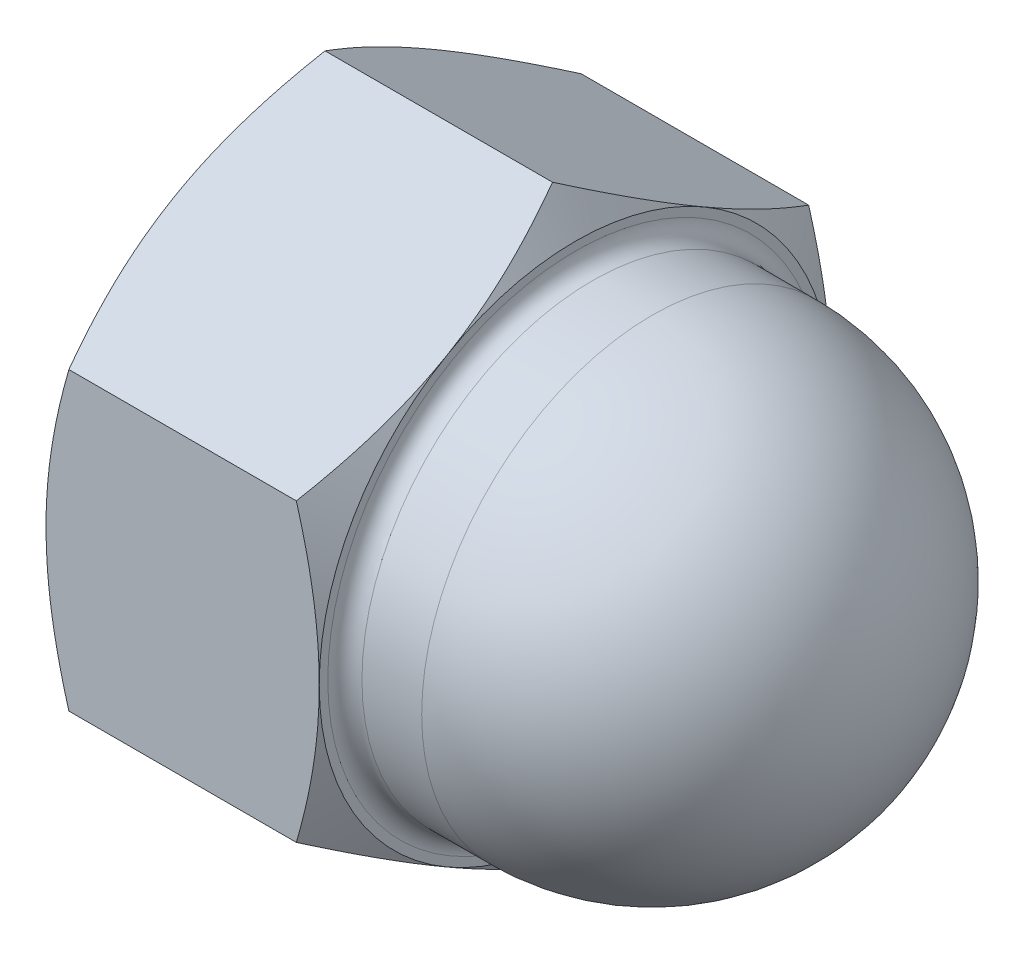
SolidWorks part; units mm, degrees
extrude "BaseNut" add sketch "BaseNutSke" along normal blind 16
sketch "BaseNutSke" plane through (0, 0, 0) normal (1, 0, 0) x (0, 0, -1)
  line L6 (15, 8.6603) -> (15, -8.6603)
  line L7 (-15, 8.6603) -> (-15, -8.6603)
  line L8 (15, 8.6603) -> (0, 17.3205)
  line L9 (0, 17.3205) -> (-15, 8.6603)
  line L10 (-15, -8.6603) -> (0, -17.3205)
  line L11 (0, -17.3205) -> (15, -8.6603)
  dimension "D4" = 60
  dimension "D1" = 120
  dimension "D2" = 15
  dimension "D3" = 15
  dimension "Width_flats" = 30
revolve "DoubleChamfer" cut sketch "Sketch4" angle 360 about L10
sketch "Sketch4" plane through (0, 0, 0) normal (0, 0, 1) x (1, 0, 0)
  line L0 (0, 15) -> (2.7831, 19.8205)
  line L1 (16, 15) -> (13.2169, 19.8205)
  line L2 (2.7831, 19.8205) -> (13.2169, 19.8205)
  line L3 (16, 15) -> (18, 15)
  line L4 (18, 15) -> (18, 30)
  line L5 (18, 30) -> (-2, 30)
  line L6 (0, 15) -> (-2, 15)
  line L7 (-2, 15) -> (-2, 30)
  line L8 (16, 17.3205) -> (16, 8.6603) construction
  line L9 (0, 17.3205) -> (0, 8.6603) construction
  line L10 (0, 0) -> (57.15, 0) construction
  line L11 (16, 17.3205) -> (0, 17.3205) construction
  point P17 (16, 15)
  dimension "D1" = 30
  dimension "D2" = 30
  dimension "D3" = 2
  dimension "D4" = 2
  dimension "D5" = 2.5
  dimension "D6" = 15
  dimension "D7" = 15
ref_plane "Plane1" through (0, 0, 0) normal (0, 0, 1) x (1, 0, 0)
ref_plane "Plane2" through (0, 0, 0) normal (0, 1, 0) x (1, 0, 0)
ref_plane "Plane3" through (0, 0, 0) normal (1, 0, 0) x (0, 0, -1)
sketch "DomeSke" plane through (0, 0, 0) normal (0, 0, 1) x (1, 0, 0)
  line L0 (0, 0) -> (63.5, 0) construction
  line L1 (0, 8.6603) -> (0, -8.6603) construction
  line L2 (34, 0) -> (0, 0)
  line L3 (0, 13.5) -> (20.5, 13.5)
  line L4 (0, -13.5) -> (22.225, -13.5) construction
  line L5 (0, 13.5) -> (0, 0)
  arc A0 (20.5, 13.5) -> (34, 0) centre (20.5, 0) cw
revolve "Dome" add sketch "DomeSke" angle 360 about L0
sketch "TapDriSke" plane through (0, 0, 0) normal (0, 0, 1) x (1, 0, 0)
  line L0 (0, 0) -> (44.45, 0) construction
  line L1 (0, 8.75) -> (27, 8.75)
  line L2 (0, 12.9904) -> (0, 0) construction
  line L3 (27, 8.75) -> (32.2575, 0)
  line L4 (0, 0) -> (63.5, 0) construction
  line L5 (32.2575, 0) -> (0, 0)
  line L6 (0, 0) -> (0, 8.75)
  line L7 (27, -8.75) -> (32.2575, 0) construction
  line L8 (0, -8.75) -> (27, -8.75) construction
  line L9 (0.5, 6.35) -> (0.5, 3.175) construction
  dimension "Drill_depth" = 27
revolve "TapDrill" cut sketch "TapDriSke"
cosmetic thread "ThreadCosmetic" [suppressed]
revolve "EndChamfer" cut sketch "EndChamferSketch" angle 360 about L4
sketch "EndChamferSketch" plane through (0, 0, 0) normal (0, 0, 1) x (1, 0, 0)
  line L0 (-0.0254, 10) -> (0.0254, 10)
  line L1 (0.0254, 10) -> (0.9882, 8.625)
  line L2 (0.9882, 8.625) -> (-0.0254, 8.625)
  line L3 (-0.0254, 8.625) -> (-0.0254, 10)
  line L4 (0, 0) -> (-15.875, 0) construction
  dimension "D1" = 0.0508
  dimension "D2" = 35
  dimension "ChamferDepth" = 1.375
  dimension "D3" = 0.0254
sketch "ThdSchSke" plane through (0, 0, 0) normal (0, 1, 0) x (1, 0, 0)
  line L0 (0.0381, 10) -> (-0.8372, 8.75)
  line L1 (-0.8372, 8.75) -> (-0.8372, 4.375)
  line L2 (-0.8372, 4.375) -> (0.9134, 4.375)
  line L3 (0.9134, 4.375) -> (0.9134, 8.75)
  line L4 (0.9134, 8.75) -> (0.0381, 10)
  line L5 (-38.1, 0) -> (3.175, 0) construction
  line L6 (0, 0) -> (-15.875, 0) construction
  line L7 (0, 0) -> (63.5, 0) construction
  line L9 (2.5381, 0.475) -> (2.5381, -5.875) construction
  dimension "D1" = 0.0381
  dimension "Thread_major" = 20
  dimension "Tap_drill" = 17.5
  dimension "OverCut" = 8.75
revolve "ThreadSchematic" [suppressed] cut sketch "ThdSchSke" angle 360 about L5
pattern_linear "ThdSchPat" [suppressed]
fillet "DomeFillet" radius 1 1 edges at (16, 0, 13.5)
equation "' \"Width_flats@BaseNutSke\" = 27"
equation "' \"Hex_ht@BaseNut\" = 16"
equation "' \"Overall_ht@DomeSke\" = 34"
equation "' \"Dome_rad@DomeSke\" = 12"
equation "' \"Thread_min@TapDriSke\" = 17.5"
equation "' \"Drill_clr@TapDriSke\" = 1.0"
equation "' \"Advance@ThdSchSke\" = 2.5"
equation "' \"Thread_nominal@ThreadCosmetic\" = 20"
equation "' \"Thread_depth@ThreadCosmetic\" = 20"
equation "' \"Radius@DomeFillet\" = 1.0"
equation "\"Drill_depth@TapDriSke\" = \"Overall_ht@DomeSke\"  - \"Drill_clr@TapDriSke\" - 0.3 * \"Thread_nominal@ThreadCosmetic\""
equation "\"D2@BaseNutSke\" = \"Width_flats@BaseNutSke\" / 2"
equation "\"D3@BaseNutSke\" = \"Width_flats@BaseNutSke\" / 2"
equation "\"D7@Sketch4\" = \"Width_flats@BaseNutSke\" / 2"
equation "\"D5@Sketch4\" = \"Width_flats@BaseNutSke\" / 12"
equation "\"Thread_major@ThdSchSke\" = \"Thread_nominal@ThreadCosmetic\""
equation "\"Tap_drill@ThdSchSke\" = \"Thread_min@TapDriSke\""
equation "\"OverCut@ThdSchSke\" = \"Tap_drill@ThdSchSke\" * 0.5"
equation "' \"Num_threads@ThdSchPat\" = int(  ( \"Hex_ht@BaseNut\" - 0.002 ) / \"Advance@ThdSchSke\" + 0.999 )  + 1"
equation "\"Num_threads@ThdSchPat\" = int(  ( \"Thread_depth@ThreadCosmetic\" - 0.002 ) / \"Advance@ThdSchSke\" + 0.999 )  + 1"
equation "' \"Advance@ThdSchPat\" = ( \"Hex_ht@BaseNut\" - 0.002 ) /  (\"Num_threads@ThdSchPat\" - 1) 'relax it"
equation "\"Advance@ThdSchPat\" = ( \"Thread_depth@ThreadCosmetic\" - 0.002 ) /  (\"Num_threads@ThdSchPat\" - 1) 'relax it"
equation "\"ThreadMajor@EndChamferSketch\" = \"Thread_nominal@ThreadCosmetic\" * 0.5"
equation "\"ChamferDepth@EndChamferSketch\" = (\"Thread_nominal@ThreadCosmetic\" - \"Thread_min@TapDriSke\") * 0.55"
